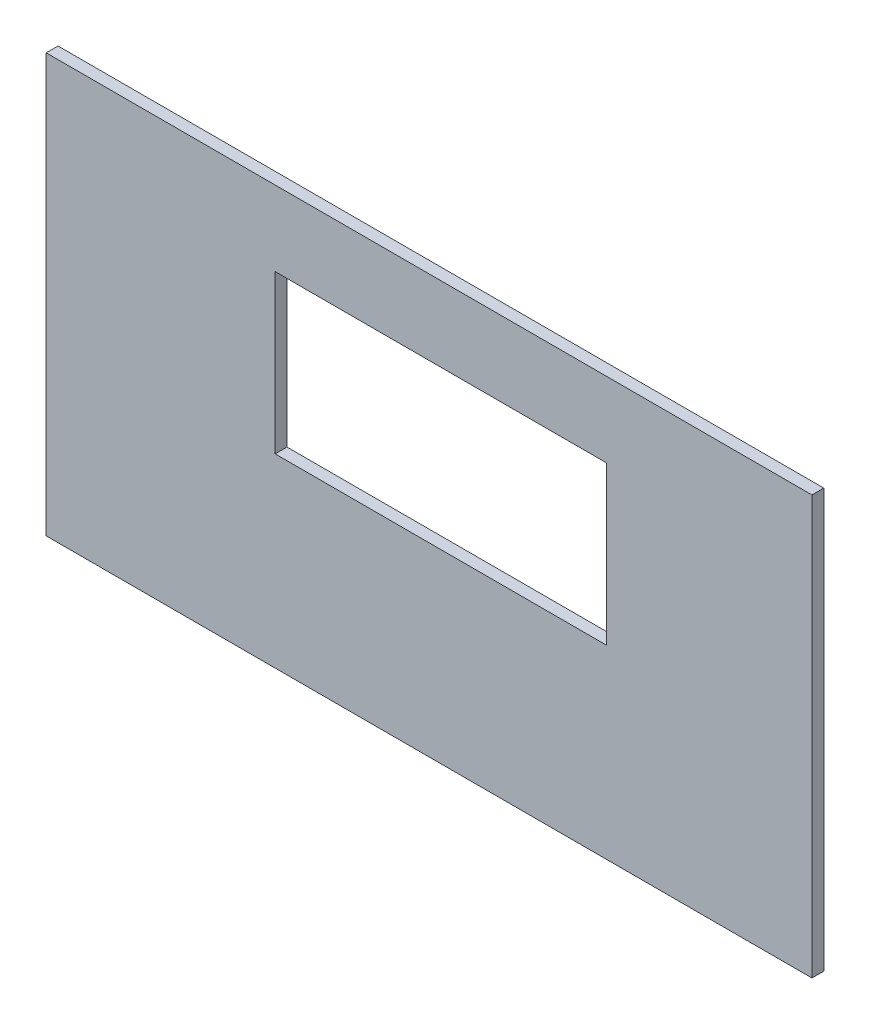
SolidWorks part; units mm, degrees
ref_plane "Front Plane" through (0, 0, 0) normal (0, 0, 1) x (1, 0, 0)
ref_plane "Top Plane" through (0, 0, 0) normal (0, 1, 0) x (1, 0, 0)
ref_plane "Right Plane" through (0, 0, 0) normal (1, 0, 0) x (0, 0, -1)
sketch "Sketch1" plane through (0, 0, 0) normal (0, 0, 1) x (1, 0, 0)
  line L1 (0, 0) -> (194, 0)
  line L2 (0, 0) -> (0, 106)
  line L3 (0, 106) -> (194, 106)
  line L4 (194, 0) -> (194, 106)
  line L6 (58, 47) -> (142, 47)
  line L7 (58, 47) -> (58, 87)
  line L8 (58, 87) -> (142, 87)
  line L9 (142, 47) -> (142, 87)
  dimension "D1" = 58
  dimension "D2" = 142
  dimension "D3" = 194
  dimension "D4" = 47
  dimension "D5" = 87
  dimension "D6" = 106
extrude "Profile" add sketch "Sketch1" along normal blind 3
equation "\"Profile_Depth\" = 3mm"
equation "\"D1@Profile\" = \"Profile_Depth\""
equation "\"Profile_Sketch_1\" = 58mm"
equation "\"D1@Sketch1\" = \"Profile_Sketch_1\""
equation "\"Profile_Sketch_2\" = 142mm"
equation "\"D2@Sketch1\" = \"Profile_Sketch_2\""
equation "\"Profile_Sketch_3\" = 194mm"
equation "\"D3@Sketch1\" = \"Profile_Sketch_3\""
equation "\"Profile_Sketch_4\" = 47mm"
equation "\"D4@Sketch1\" = \"Profile_Sketch_4\""
equation "\"Profile_Sketch_5\" = 87mm"
equation "\"D5@Sketch1\" = \"Profile_Sketch_5\""
equation "\"Profile_Sketch_6\" = 106mm"
equation "\"D6@Sketch1\" = \"Profile_Sketch_6\""
equation "\"EnvelopeWidth\" = 194mm"
equation "\"EnvelopeHeight\" = 106mm"
